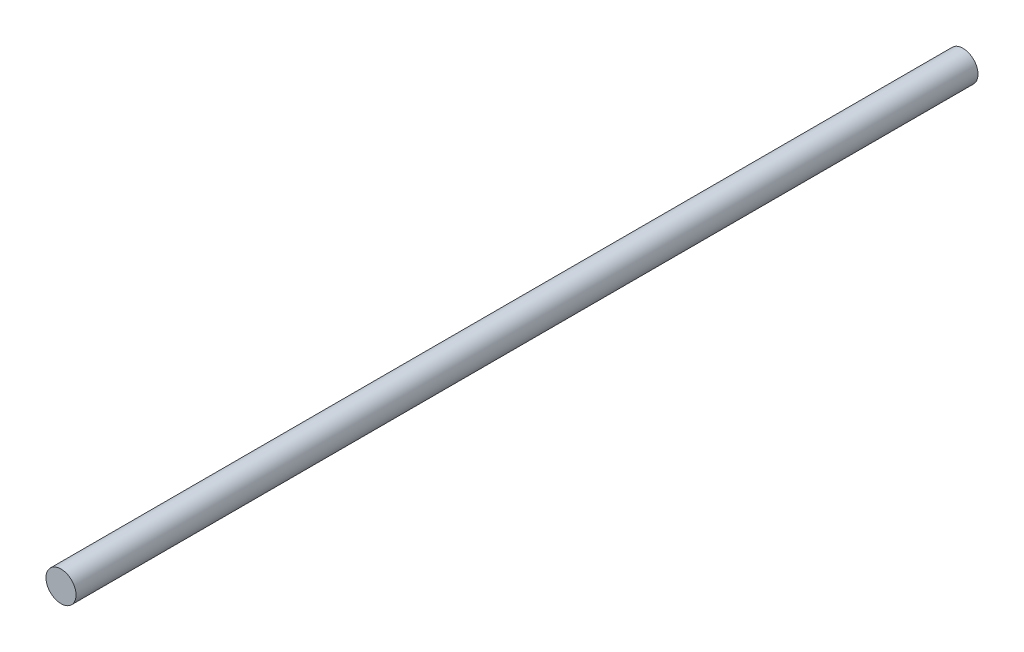
SolidWorks part; units mm, degrees
ref_plane "Спереди" through (0, 0, 0) normal (0, 0, 1) x (1, 0, 0)
ref_plane "Сверху" through (0, 0, 0) normal (0, 1, 0) x (1, 0, 0)
ref_plane "Справа" through (0, 0, 0) normal (1, 0, 0) x (0, 0, -1)
sketch "Эскиз1" plane through (0, 0, 0) normal (0, 0, 1) x (1, 0, 0)
  circle A0 centre (0, 0) radius 2
extrude "Вытянуть1" add sketch "Эскиз1" along normal blind 120
